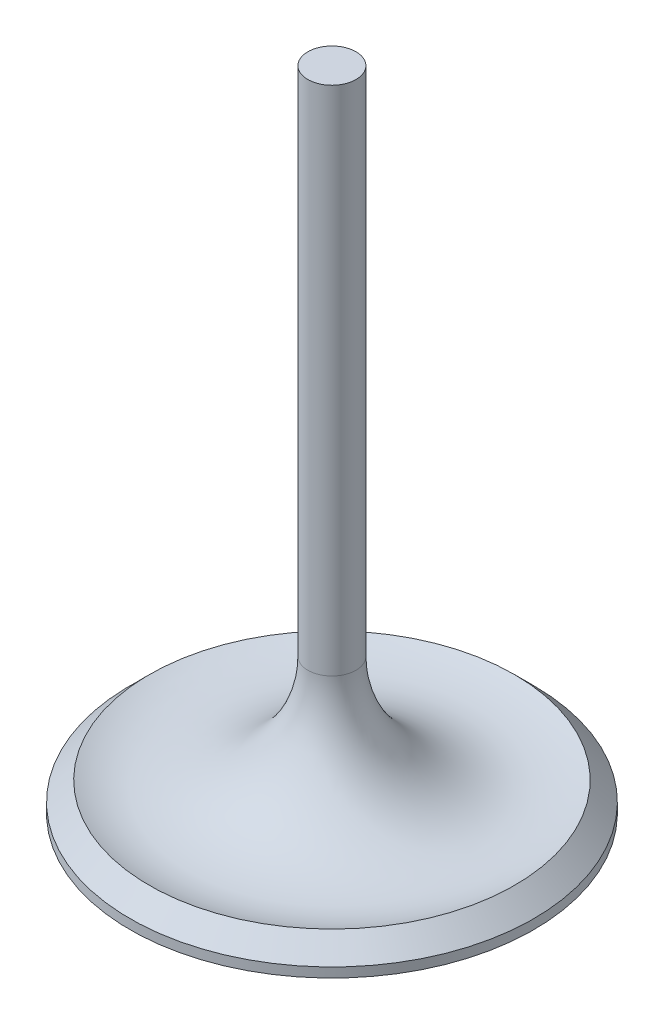
SolidWorks part; units mm, degrees
ref_plane "Front Plane" through (0, 0, 0) normal (0, 0, 1) x (1, 0, 0)
ref_plane "Top Plane" through (0, 0, 0) normal (0, 1, 0) x (1, 0, 0)
ref_plane "Right Plane" through (0, 0, 0) normal (1, 0, 0) x (0, 0, -1)
sketch "Sketch1" plane through (0, 0, 0) normal (0, 0, 1) x (1, 0, 0)
  line L0 (0, 0) -> (0, 85.55)
  line L1 (0, 85.55) -> (3.18, 85.55)
  line L2 (3.18, 85.55) -> (3.18, 17.9547)
  line L3 (24.13, 3.81) -> (26.67, 1.27)
  line L4 (26.67, 1.27) -> (26.67, 0)
  line L5 (26.67, 0) -> (0, 0)
  arc A0 (3.18, 17.9547) -> (24.13, 3.81) centre (18.43, 17.9547) ccw
  point P8 (0, 0)
  dimension "D7" = 15.25
  dimension "D1" = 85.55
  dimension "D2" = 3.18
  dimension "D3" = 26.67
  dimension "D4" = 1.27
  dimension "D5" = 3.81
  dimension "D6" = 45
revolve "Revolve1" add sketch "Sketch1" angle 360 about L0
